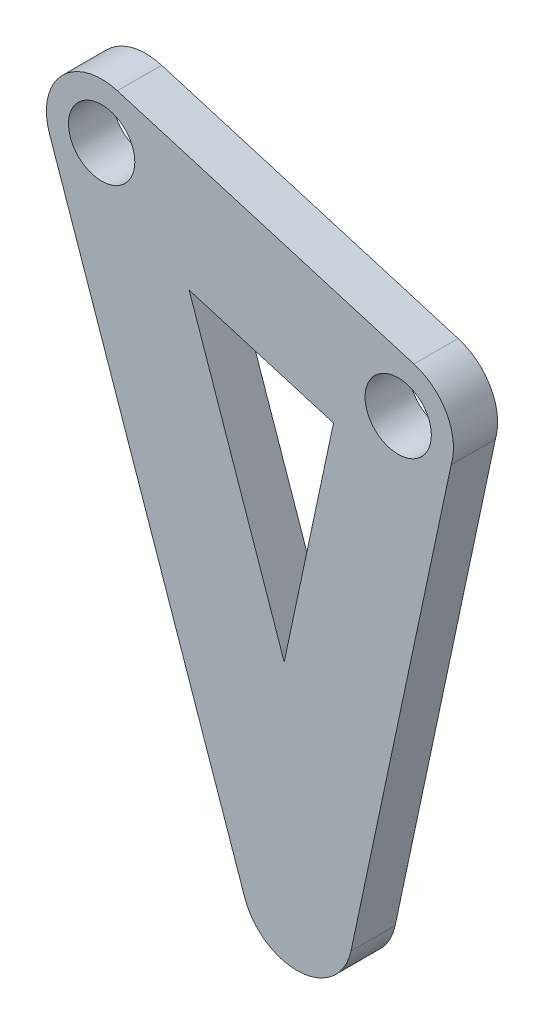
SolidWorks part; units mm, degrees
ref_plane "Plan de face" through (0, 0, 0) normal (0, 0, 1) x (1, 0, 0)
ref_plane "Plan de dessus" through (0, 0, 0) normal (0, 1, 0) x (1, 0, 0)
ref_plane "Plan de droite" through (0, 0, 0) normal (1, 0, 0) x (0, 0, -1)
sketch "Esquisse1" plane through (0, 0, 0) normal (0, 0, 1) x (1, 0, 0)
  line L0 (-34.5773, -10.018) -> (-21.1599, -14.0144) construction
  line L1 (-33.8637, -7.622) -> (-20.4462, -11.6185)
  line L2 (-35.291, -12.414) -> (-21.8735, -16.4104)
  line L3 (-21.1599, -14.0144) -> (-25.7429, -35.5318) construction
  line L4 (-18.7147, -14.5353) -> (-23.2978, -36.0526)
  line L5 (-23.605, -13.4936) -> (-28.1881, -35.011)
  line L6 (-34.5773, -10.018) -> (-25.7429, -35.5318) construction
  line L7 (-32.2149, -9.2) -> (-23.3805, -34.7138)
  line L8 (-36.9397, -10.836) -> (-28.1053, -36.3498)
  line L9 (-33.8637, -7.622) -> (-20.4462, -11.6185)
  line L10 (-23.2978, -36.0526) -> (-18.7639, -14.7281)
  line L11 (-28.1053, -36.3498) -> (-36.9397, -10.836)
  line L12 (-30.6204, -13.8051) -> (-24.0859, -15.7514)
  line L13 (-24.0859, -15.7514) -> (-26.3179, -26.2306)
  line L14 (-26.3179, -26.2306) -> (-30.6204, -13.8051)
  arc A0 (-33.8637, -7.622) -> (-35.291, -12.414) centre (-34.5773, -10.018) ccw
  arc A1 (-21.8735, -16.4104) -> (-20.4462, -11.6185) centre (-21.1599, -14.0144) ccw
  arc A2 (-18.7147, -14.5353) -> (-23.605, -13.4936) centre (-21.1599, -14.0144) ccw
  arc A3 (-28.1881, -35.011) -> (-23.2978, -36.0526) centre (-25.7429, -35.5318) ccw
  arc A4 (-32.2149, -9.2) -> (-36.9397, -10.836) centre (-34.5773, -10.018) ccw
  arc A5 (-28.1053, -36.3498) -> (-23.3805, -34.7138) centre (-25.7429, -35.5318) ccw
  arc A6 (-33.8637, -7.622) -> (-36.9397, -10.836) centre (-34.5773, -10.018) ccw
  arc A7 (-18.7639, -14.7281) -> (-19.4103, -12.2287) centre (-21.1599, -14.0144) ccw
  arc A8 (-28.1053, -36.3498) -> (-23.2465, -35.3974) centre (-25.7429, -35.5318) ccw
  point P4 (-27.8686, -12.0162)
  point P9 (-23.4514, -24.7731)
  point P17 (-30.1601, -22.7749)
  point P30 (-26.3179, -26.2306)
  point P31 (-30.6204, -13.8051)
  point P32 (-24.0859, -15.7514)
  dimension "D1" = 5
  dimension "D2" = 5
  dimension "D3" = 5
extrude "Boss.-Extru.1" add sketch "Esquisse1" against normal blind 2 contours A3 L5 L7 L2 A0 L8 | L7 A4 A0 L2 | A4 L7 L2 L5 A2 L1 | A1 A2 L5 L2 | A5 L10 A1 L2 L5 L7 | A3 A5 L7 L5
sketch "Esquisse2" plane through (0, 0, 0) normal (0, 0, 1) x (1, 0, 0)
  circle A0 centre (-34.5773, -10.018) radius 1.5
  circle A1 centre (-21.1599, -14.0144) radius 1.5
  dimension "D1" = 3
  dimension "D2" = 3
extrude "Enlèv. mat.-Extru.1" cut sketch "Esquisse2" against normal blind 2
